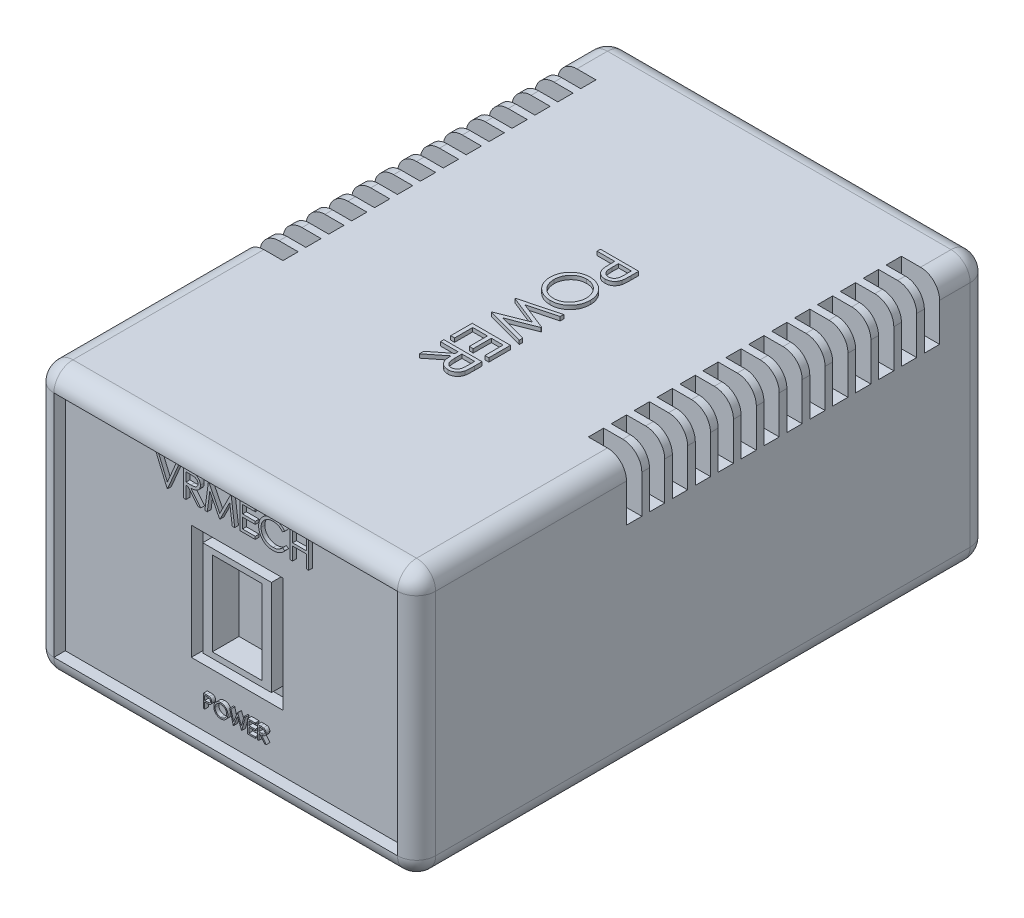
SolidWorks part; units mm, degrees
ref_plane "Ön Düzlem" through (0, 0, 0) normal (0, 0, 1) x (1, 0, 0)
ref_plane "Üst Düzlem" through (0, 0, 0) normal (0, 1, 0) x (1, 0, 0)
ref_plane "Sağ Düzlem" through (0, 0, 0) normal (1, 0, 0) x (0, 0, -1)
sketch "Çizim1" plane through (0, 0, 0) normal (0, 0, 1) x (1, 0, 0)
  line L1 (-50, 35) -> (50, 35)
  line L2 (-50, 35) -> (-50, -35)
  line L3 (-50, -35) -> (50, -35)
  line L4 (50, 35) -> (50, -35)
  line L5 (-50, 35) -> (50, -35) construction
  line L6 (-50, -35) -> (50, 35) construction
  point P0 (0, 0)
  dimension "D1" = 100
  dimension "D2" = 70
extrude "Yükseklik-Ekstrüzyon1" add sketch "Çizim1" along normal blind 150
fillet "Radyus1" radius 5 12 edges at (50, 35, 75) (50, -35, 75) (0, -35, 150) (0, 35, 150) (50, 0, 150) (-50, 35, 75) (-50, 0, 150) (-50, -35, 75) (0, 35, 0) (-50, 0, 0) (0, -35, 0) (50, 0, 0)
sketch "Çizim2" plane through (0, 0, 150) normal (0, 0, 1) x (1, 0, 0)
  line L1 (-45, 30) -> (45, 30)
  line L2 (-45, 30) -> (-45, -30)
  line L3 (-45, -30) -> (45, -30)
  line L4 (45, 30) -> (45, -30)
  line L5 (-45, 30) -> (45, -30) construction
  line L6 (-45, -30) -> (45, 30) construction
  point P0 (0, 0)
extrude "Kes-Ekstrüzyon1" cut sketch "Çizim2" against normal blind 3
sketch "Çizim4" plane through (0, 35, 0) normal (0, 1, 0) x (1, 0, 0)
  line L0 (-45, -5) -> (-45, -145) construction
  line L1 (0, 0) -> (0, -145) construction
  line L2 (-50, -13) -> (-40, -13)
  line L3 (-50, -13) -> (-50, -17)
  line L4 (-50, -17) -> (-40, -17)
  line L5 (-40, -13) -> (-40, -17)
  line L6 (-50, -13) -> (-40, -17) construction
  line L7 (-50, -17) -> (-40, -13) construction
  line L8 (-45, -145) -> (45, -145) construction
  line L9 (45, -5) -> (-45, -5) construction
  line L10 (-50, -19) -> (-40, -19)
  line L11 (-50, -19) -> (-50, -23)
  line L12 (-50, -23) -> (-40, -23)
  line L13 (-40, -19) -> (-40, -23)
  line L14 (-50, -19) -> (-40, -23) construction
  line L15 (-50, -23) -> (-40, -19) construction
  line L16 (-50, -25) -> (-40, -25)
  line L17 (-50, -25) -> (-50, -29)
  line L18 (-50, -29) -> (-40, -29)
  line L19 (-40, -25) -> (-40, -29)
  line L20 (-50, -25) -> (-40, -29) construction
  line L21 (-50, -29) -> (-40, -25) construction
  line L22 (-50, -31) -> (-40, -31)
  line L23 (-50, -31) -> (-50, -35)
  line L24 (-50, -35) -> (-40, -35)
  line L25 (-40, -31) -> (-40, -35)
  line L26 (-50, -31) -> (-40, -35) construction
  line L27 (-50, -35) -> (-40, -31) construction
  line L28 (-50, -37) -> (-40, -37)
  line L29 (-50, -37) -> (-50, -41)
  line L30 (-50, -41) -> (-40, -41)
  line L31 (-40, -37) -> (-40, -41)
  line L32 (-50, -37) -> (-40, -41) construction
  line L33 (-50, -41) -> (-40, -37) construction
  line L34 (-50, -43) -> (-40, -43)
  line L35 (-50, -43) -> (-50, -47)
  line L36 (-50, -47) -> (-40, -47)
  line L37 (-40, -43) -> (-40, -47)
  line L38 (-50, -43) -> (-40, -47) construction
  line L39 (-50, -47) -> (-40, -43) construction
  line L40 (-50, -49) -> (-40, -49)
  line L41 (-50, -49) -> (-50, -53)
  line L42 (-50, -53) -> (-40, -53)
  line L43 (-40, -49) -> (-40, -53)
  line L44 (-50, -49) -> (-40, -53) construction
  line L45 (-50, -53) -> (-40, -49) construction
  line L46 (-54.1738, -54) -> (-35.0254, -54) construction
  line L47 (-50, -55) -> (-40, -55)
  line L48 (-40, -59) -> (-40, -55)
  line L49 (-50, -59) -> (-50, -55)
  line L50 (-50, -59) -> (-40, -59)
  line L51 (-50, -61) -> (-40, -61)
  line L52 (-40, -65) -> (-40, -61)
  line L53 (-50, -65) -> (-40, -65)
  line L54 (-50, -65) -> (-50, -61)
  line L55 (-50, -71) -> (-50, -67)
  line L56 (-50, -67) -> (-40, -67)
  line L57 (-40, -71) -> (-40, -67)
  line L58 (-50, -71) -> (-40, -71)
  line L59 (-50, -73) -> (-40, -73)
  line L60 (-50, -77) -> (-50, -73)
  line L61 (-40, -77) -> (-40, -73)
  line L62 (-50, -77) -> (-40, -77)
  line L63 (-50, -79) -> (-40, -79)
  line L64 (-40, -83) -> (-40, -79)
  line L65 (-50, -83) -> (-40, -83)
  line L66 (-50, -83) -> (-50, -79)
  line L67 (-50, -89) -> (-50, -85)
  line L68 (-50, -85) -> (-40, -85)
  line L69 (-40, -89) -> (-40, -85)
  line L70 (-50, -89) -> (-40, -89)
  line L71 (-50, -95) -> (-50, -91)
  line L72 (-40, -95) -> (-40, -91)
  line L73 (-50, -91) -> (-40, -91)
  line L74 (-50, -95) -> (-40, -95)
  line L75 (40, -95) -> (40, -91)
  line L76 (50, -95) -> (40, -95)
  line L77 (50, -95) -> (50, -91)
  line L78 (50, -91) -> (40, -91)
  line L79 (50, -89) -> (50, -85)
  line L80 (40, -89) -> (40, -85)
  line L81 (50, -89) -> (40, -89)
  line L82 (50, -85) -> (40, -85)
  line L83 (50, -83) -> (40, -83)
  line L84 (40, -83) -> (40, -79)
  line L85 (50, -79) -> (40, -79)
  line L86 (50, -83) -> (50, -79)
  line L87 (50, -77) -> (50, -73)
  line L88 (50, -77) -> (40, -77)
  line L89 (40, -77) -> (40, -73)
  line L90 (50, -73) -> (40, -73)
  line L91 (50, -71) -> (40, -71)
  line L92 (50, -71) -> (50, -67)
  line L93 (40, -71) -> (40, -67)
  line L94 (50, -65) -> (50, -61)
  line L95 (40, -65) -> (40, -61)
  line L96 (50, -67) -> (40, -67)
  line L97 (50, -65) -> (40, -65)
  line L98 (50, -61) -> (40, -61)
  line L99 (50, -59) -> (40, -59)
  line L100 (50, -59) -> (50, -55)
  line L101 (40, -59) -> (40, -55)
  line L102 (50, -55) -> (40, -55)
  line L103 (50, -53) -> (40, -53)
  line L104 (50, -49) -> (50, -53)
  line L105 (40, -49) -> (40, -53)
  line L106 (50, -49) -> (40, -49)
  line L107 (40, -43) -> (40, -47)
  line L108 (50, -43) -> (50, -47)
  line L109 (50, -43) -> (40, -43)
  line L110 (40, -37) -> (40, -41)
  line L111 (50, -41) -> (40, -41)
  line L112 (50, -37) -> (50, -41)
  line L113 (50, -37) -> (40, -37)
  line L114 (50, -31) -> (50, -35)
  line L115 (50, -35) -> (40, -35)
  line L116 (40, -31) -> (40, -35)
  line L117 (50, -31) -> (40, -31)
  line L118 (50, -29) -> (40, -29)
  line L119 (40, -25) -> (40, -29)
  line L120 (50, -25) -> (40, -25)
  line L121 (50, -25) -> (50, -29)
  line L122 (50, -19) -> (50, -23)
  line L123 (40, -19) -> (40, -23)
  line L124 (50, -23) -> (40, -23)
  line L125 (50, -19) -> (40, -19)
  line L126 (50, -13) -> (50, -17)
  line L127 (40, -13) -> (40, -17)
  line L128 (50, -17) -> (40, -17)
  line L129 (50, -13) -> (40, -13)
  line L130 (40, -47) -> (50, -47)
  point P4 (-45, -15)
  point P14 (-45, -21)
  point P19 (-45, -27)
  point P24 (-45, -33)
  point P29 (-45, -39)
  point P34 (-45, -45)
  point P39 (-45, -51)
  line M61 (45, -145) -> (45, -5)
  line M63 (-45, -5) -> (-45, -145)
  dimension "D1" = 10
  dimension "D2" = 10
  dimension "D3" = 4
  dimension "D4" = 8
  dimension "D5" = 4
  dimension "D6" = 4
  dimension "D7" = 4
  dimension "D8" = 2
  dimension "D9" = 2
  dimension "D10" = 2
  dimension "D11" = 2
  dimension "D12" = 2
  dimension "D13" = 2
  dimension "D14" = 4
  dimension "D15" = 4
  dimension "D16" = 4
  dimension "D17" = 1
extrude "Kes-Ekstrüzyon2" cut sketch "Çizim4" against normal blind 15 contours L5 L2 L4 M63 | L3 L4 L2 M63 | L13 L10 L12 M63 | L11 L12 L10 M63 | L17 L18 L16 M63 | L19 L16 L18 M63 | L25 L22 L24 M63 | L23 L24 L22 M63 | L29 L30 L28 M63 | L31 L28 L30 M63 | L37 L34 L36 M63 | L35 L36 L34 M63 | L41 L42 L40 M63 | L43 L40 L42 M63 | L50 L48 L47 M63 | L49 L50 L47 M63 | L54 L53 L51 M63 | L53 L52 L51 M63 | L58 L57 L56 M63 | L55 L58 L56 M63 | L65 L64 L63 M63 | L66 L65 L63 M63 | L67 L70 L68 M63 | L70 L69 L68 M63 | L71 L74 L73 M63 | L129 L127 L128 M61 | L126 L129 L128 M61 | L125 L123 L124 M61 | L122 L125 L124 M61 | L120 L119 L118 M61 | L121 L120 L118 M61 | L117 L116 L115 M61 | L113 L110 L111 M61 | L112 L113 L111 M61 | L104 L106 L103 M61 | L106 L105 L103 M61 | L102 L101 L99 M61 | L100 L102 L99 M61 | L92 L96 L91 M61 | L96 L93 L91 M61 | L90 L89 L88 M61 | L87 L90 L88 M61 | L83 L86 L85 M61 | L85 L84 L83 M61 | L82 L80 L81 M61 | L79 L82 L81 M61 | L77 L78 L76 M61 | L78 L75 L76 M61 | L62 L61 L59 L60 | L98 L95 L97 L94
sketch "Çizim5" plane through (0, 35, 0) normal (0, 1, 0) x (1, 0, 0)
  line L0 (50, -41) -> (50, -49) construction
  line L1 (40, -43) -> (50, -43)
  line L2 (40, -43) -> (40, -47)
  line L3 (40, -47) -> (50, -47)
  line L4 (50, -43) -> (50, -47)
  line L5 (40, -43) -> (50, -47) construction
  line L6 (40, -47) -> (50, -43) construction
  line L7 (45, -41) -> (40, -41) construction
  line L8 (50, -49) -> (40, -49) construction
  point P0 (45, -45)
  dimension "D1" = 2
  dimension "D2" = 2
  dimension "D3" = 10
  dimension "D4" = 4
extrude "Kes-Ekstrüzyon3" cut sketch "Çizim5" against normal blind 15
sketch "Çizim6" plane through (0, 0, 147) normal (0, 0, 1) x (1, 0, 0)
  line L1 (-9, 12.5) -> (9, 12.5)
  line L2 (-9, 12.5) -> (-9, -12.5)
  line L3 (-9, -12.5) -> (9, -12.5)
  line L4 (9, 12.5) -> (9, -12.5)
  line L5 (-9, 12.5) -> (9, -12.5) construction
  line L6 (-9, -12.5) -> (9, 12.5) construction
  line L7 (-12, 15) -> (12, 15)
  line L8 (-12, 15) -> (-12, -15)
  line L9 (-12, -15) -> (12, -15)
  line L10 (12, 15) -> (12, -15)
  line L11 (-12, 15) -> (12, -15) construction
  line L12 (-12, -15) -> (12, 15) construction
  point P0 (0, 0)
  point P7 (0, 0)
  dimension "D1" = 24
  dimension "D2" = 30
  dimension "D3" = 25
  dimension "D4" = 18
extrude "Kes-Ekstrüzyon4" cut sketch "Çizim6" against normal blind 3
sketch "Çizim7" plane through (0, 0, 147) normal (0, 0, 1) x (1, 0, 0)
  line L1 (-6.5, 11) -> (6.5, 11)
  line L2 (-6.5, 11) -> (-6.5, -11)
  line L3 (-6.5, -11) -> (6.5, -11)
  line L4 (6.5, 11) -> (6.5, -11)
  line L5 (-6.5, 11) -> (6.5, -11) construction
  line L6 (-6.5, -11) -> (6.5, 11) construction
  point P0 (0, 0)
  dimension "D1" = 13
  dimension "D2" = 22
extrude "Kes-Ekstrüzyon5" cut sketch "Çizim7" against normal blind 7
sketch "Çizim8" plane through (6.5, 0, 0) normal (-1, 0, 0) x (0, 0, 1)
  line L0 (145, -30) -> (145, 30) construction
  circle A0 centre (145, 0) radius 0.5
  dimension "D1" = 1
extrude "Kes-Ekstrüzyon6" cut sketch "Çizim8" against normal blind 1 contours A0
sketch "Çizim10" plane through (0, 0, 147) normal (0, 0, 1) x (1, 0, 0)
  line L1 (32.801, 21.1156) -> (-32.801, 21.1156) construction
  text T0 "VRMECH" font "Century Gothic" height 7
extrude "Yükseklik-Ekstrüzyon2" add sketch "Çizim10" along normal blind 1
sketch "Çizim11" plane through (0, 35, 0) normal (0, 1, 0) x (1, 0, 0)
  line L0 (0, 0) -> (0, -150.0542) construction
  text T0 "POWER" font "Century Gothic" height 10
extrude "Yükseklik-Ekstrüzyon3" add sketch "Çizim11" along normal blind 1
sketch "Çizim12" plane through (0, 0, 147) normal (0, 0, 1) x (1, 0, 0)
  line L0 (-21.6281, -23.9982) -> (19.5781, -23.9982) construction
  text T0 "  POWER"
extrude "Yükseklik-Ekstrüzyon4" add sketch "Çizim12" along normal blind 1
sketch "Çizim13" plane through (6.5, 0, 0) normal (-1, 0, 0) x (0, 0, 1)
  line L0 (145, 0) -> (140, 0)
  line L1 (145, -30) -> (145, 30) construction
  dimension "D1" = 5
